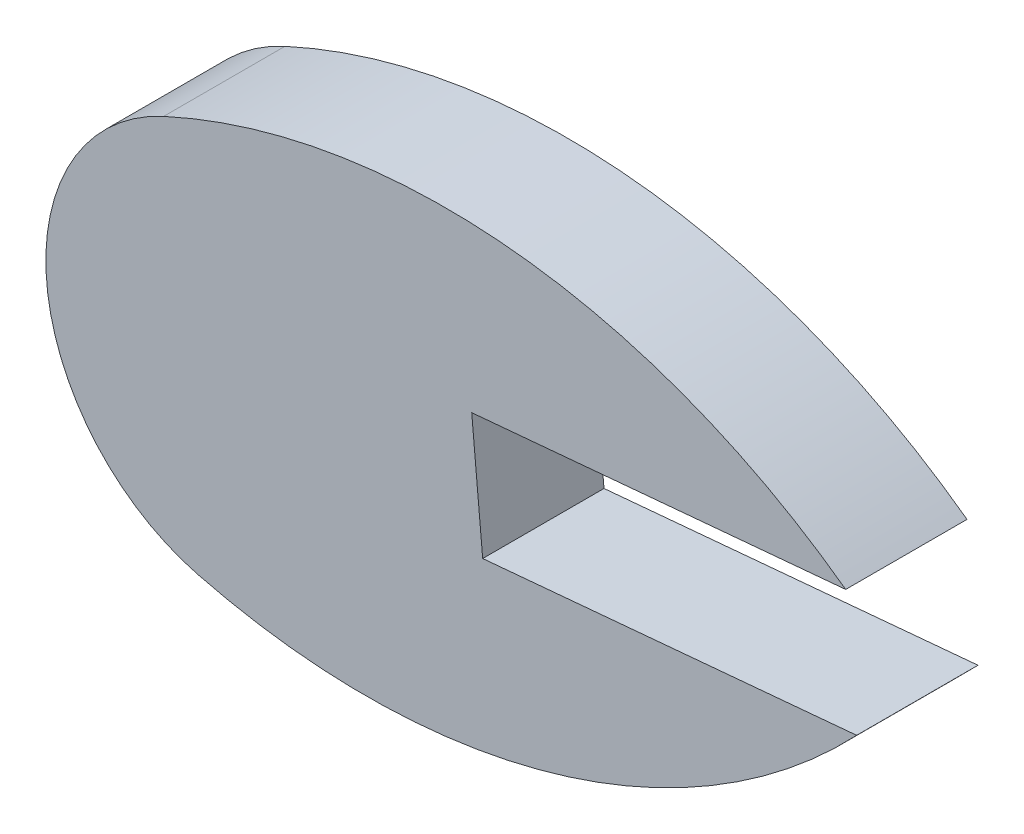
SolidWorks part; units mm, degrees
ref_plane "Front" through (0, 0, 0) normal (0, 0, 1) x (1, 0, 0)
ref_plane "Top" through (0, 0, 0) normal (0, 1, 0) x (1, 0, 0)
ref_plane "Right" through (0, 0, 0) normal (1, 0, 0) x (0, 0, -1)
sketch "Sketch1" plane through (0, 0, 0) normal (0, 0, 1) x (1, 0, 0)
  line L1 (-856.4742, -32.6419) -> (-865.7208, -33.4802)
  line L18 (-856.7451, -29.6542) -> (-865.9916, -30.4925)
  line L19 (-865.9916, -30.4925) -> (-865.7208, -33.4802)
  arc A0 (-873.6094, -27.9571) -> (-856.7451, -29.6542) centre (-866.6214, -43.1561) cw
  arc A1 (-872.7583, -37.3443) -> (-856.4742, -32.6419) centre (-868.6178, -21.1363) ccw
  arc A2 (-872.7583, -37.3443) -> (-873.6094, -27.9571) centre (-871.5208, -32.4999) cw
extrude "Base-Extrude" add sketch "Sketch1" along normal blind 3
